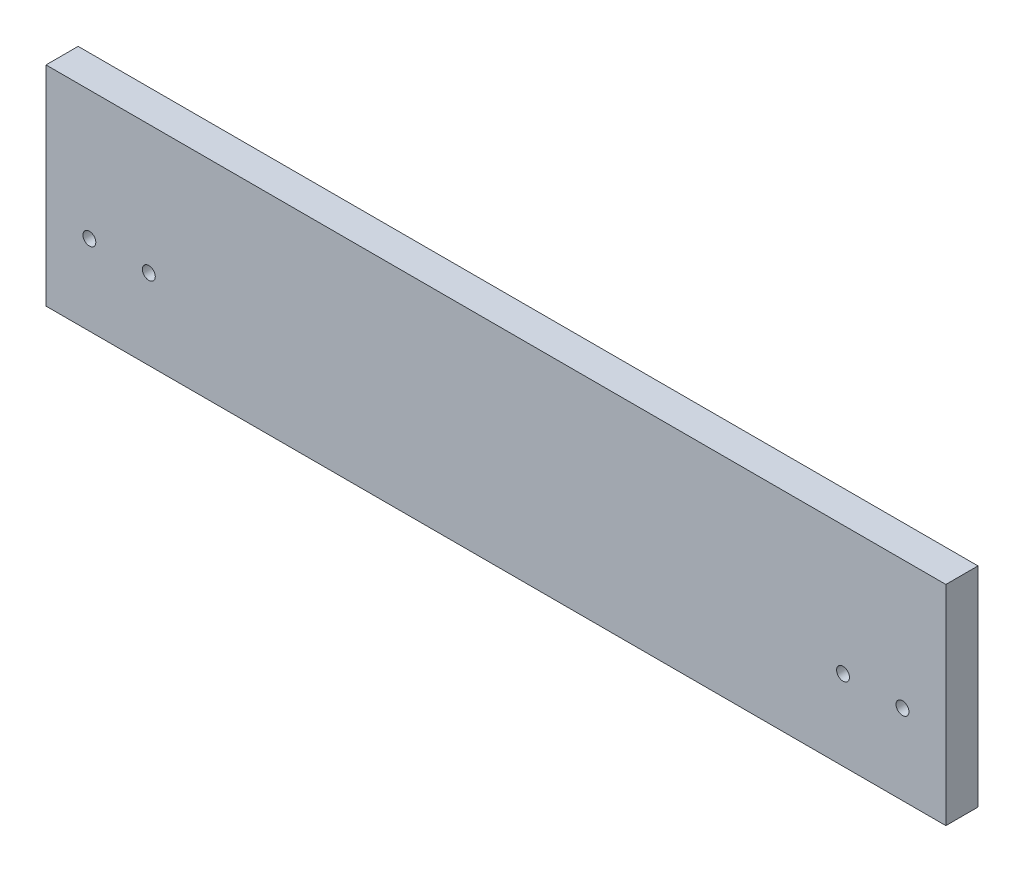
SolidWorks part; units mm, degrees
material "Multistrato di pioppo"
ref_plane "Piano frontale" through (0, 0, 0) normal (0, 0, 1) x (1, 0, 0)
ref_plane "Piano superiore" through (0, 0, 0) normal (0, 1, 0) x (1, 0, 0)
ref_plane "Piano destro" through (0, 0, 0) normal (1, 0, 0) x (0, 0, -1)
sketch "Schizzo1" plane through (0, 0, 0) normal (0, 0, 1) x (1, 0, 0)
  line L1 (0, 0) -> (-280, 0)
  line L2 (0, 0) -> (0, 65)
  line L3 (0, 65) -> (-280, 65)
  line L4 (-280, 0) -> (-280, 65)
  dimension "D1" = 280
  dimension "D2" = 65
extrude "Estrusione-Estrusione1" add sketch "Schizzo1" along normal blind 10
sketch "Schizzo2" plane through (0, 0, 0) normal (0, 0, -1) x (-1, 0, 0)
  circle A0 centre (248, 24.9337) radius 2
  circle A1 centre (266.5, 24.9337) radius 2
  circle A2 centre (13.5, 24.9337) radius 2
  circle A3 centre (32, 24.9337) radius 2
  dimension "D1" = 4
extrude "Taglio-Estrusione1" cut sketch "Schizzo2" against normal blind 10
